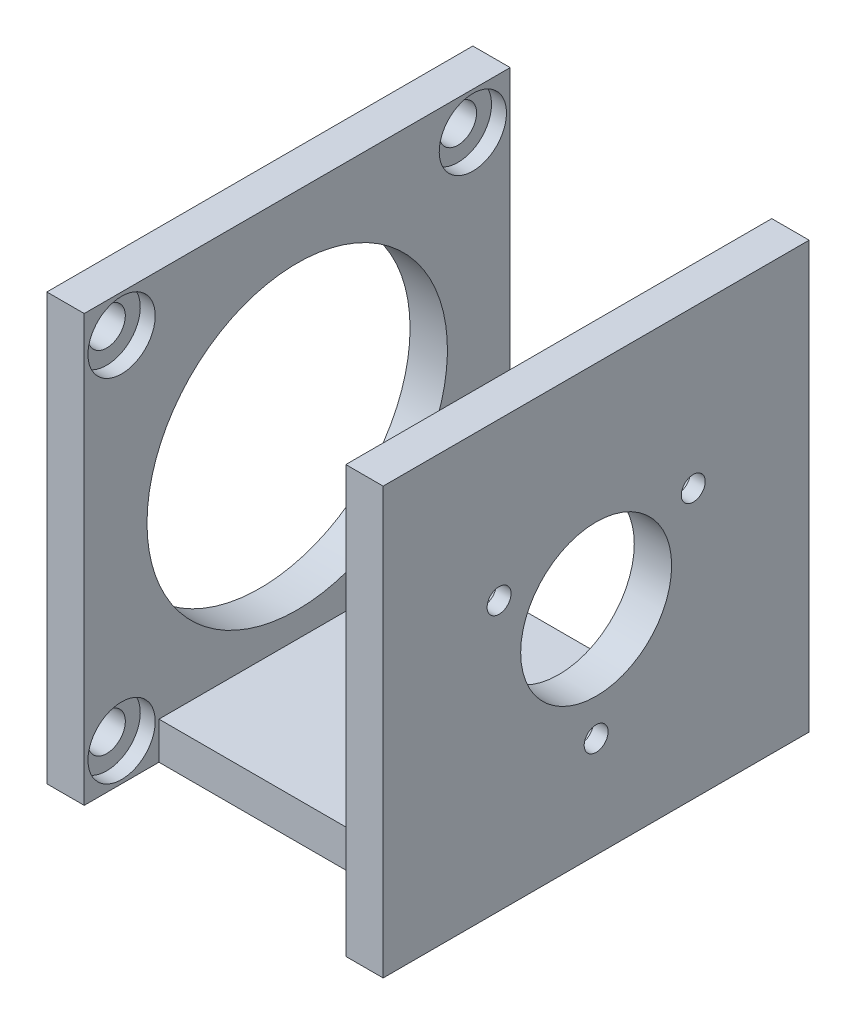
SolidWorks part; units mm, degrees
ref_plane "前视基准面" through (0, 0, 0) normal (0, 0, 1) x (1, 0, 0)
ref_plane "上视基准面" through (0, 0, 0) normal (0, 1, 0) x (1, 0, 0)
ref_plane "右视基准面" through (0, 0, 0) normal (1, 0, 0) x (0, 0, -1)
other "Configuration Table"
sketch "草图1" plane through (0, 0, 0) normal (0, 0, 1) x (1, 0, 0)
  line L0 (0, 0) -> (0, 57)
  line L1 (0, 57) -> (5, 57)
  line L2 (5, 57) -> (5, 5)
  line L3 (5, 5) -> (40, 5)
  line L4 (40, 5) -> (40, 57)
  line L5 (40, 57) -> (45, 57)
  line L6 (45, 57) -> (45, 0)
  line L7 (45, 0) -> (0, 0)
  dimension "D1" = 5
  dimension "D2" = 5
  dimension "D3" = 57
  dimension "D4" = 35
  dimension "D5" = 5
  dimension "D6" = 57
extrude "凸台-拉伸1" add sketch "草图1" along normal blind 57
sketch "草图2" plane through (0, 5, 0) normal (0, 1, 0) x (1, 0, 0)
  line L0 (40, -57) -> (40, 0) construction
  line L1 (5, -57) -> (40, -57)
  line L2 (5, -57) -> (5, -47)
  line L3 (5, -47) -> (40, -47)
  line L4 (40, -57) -> (40, -47)
  line L5 (40, -57) -> (40, 0) construction
  line L6 (5, 0) -> (40, 0)
  line L7 (5, 0) -> (5, -10)
  line L8 (5, -10) -> (40, -10)
  line L9 (40, 0) -> (40, -10)
  dimension "D1" = 10
  dimension "D2" = 10
extrude "切除-拉伸1" cut sketch "草图2" against normal through all
sketch "草图3" plane through (0, 0, 0) normal (-1, 0, 0) x (0, 0, 1)
  line L0 (57, 0) -> (0, 0) construction
  line L3 (0, 57) -> (0, 0) construction
  circle A0 centre (28.5, 28.5) radius 20.1
  point P6 (0, 28.1279)
  point P7 (0, 28.7658)
  dimension "D1" = 40.2
  dimension "D2" = 28.5
  dimension "D3" = 28.5
extrude "切除-拉伸2" cut sketch "草图3" against normal up to next
sketch "草图4" plane through (5, 0, 0) normal (1, 0, 0) x (0, 0, -1)
  line L4 (0, 0) -> (0, 57)
  line L5 (0, 57) -> (-57, 57)
  line L6 (-57, 57) -> (-57, 0)
  line L7 (-57, 0) -> (0, 0)
  line L8 (0, 0) -> (0, 57) construction
  line L9 (0, 57) -> (-57, 57) construction
  line L10 (-57, 57) -> (-57, 0) construction
  line L11 (-57, 0) -> (0, 0) construction
  circle A0 centre (-52, 52) radius 4.5
  circle A4 centre (-28.5, 28.5) radius 20.1 construction
  circle A5 centre (-28.5, 28.5) radius 20.1 construction
  circle A9 centre (-5, 52) radius 4.5
  circle A10 centre (-5, 5) radius 4.5
  circle A11 centre (-52, 5) radius 4.5
  point P18 (-28.5, 28.5)
  dimension "D2" = 9
  dimension "D5" = 4
  dimension "D3" = 5
  dimension "D4" = 5
  dimension "D1" = 0
extrude "切除-拉伸6" cut sketch "草图4" against normal blind 2
sketch "草图5" plane through (0, 0, 0) normal (1, 0, 0) x (0, 0, -1)
  line L8 (0, 0) -> (0, 57) construction
  line L9 (0, 57) -> (-57, 57) construction
  line L10 (-57, 57) -> (-57, 0) construction
  line L11 (-57, 0) -> (0, 0) construction
  circle A0 centre (-52, 52) radius 2.5
  circle A1 centre (-28.5, 28.5) radius 20.1 construction
  circle A2 centre (-28.5, 28.5) radius 20.1 construction
  circle A3 centre (-5, 52) radius 2.5
  circle A4 centre (-5, 5) radius 2.5
  circle A5 centre (-52, 5) radius 2.5
  point P18 (-28.5, 28.5)
  dimension "D2" = 5
  dimension "D3" = 5
  dimension "D4" = 5
  dimension "D1" = 4
extrude "切除-拉伸7" cut sketch "草图5" along normal up to next
sketch "草图9" plane through (45, 0, 0) normal (1, 0, 0) x (0, 0, -1)
  line L0 (-57, 0) -> (0, 0) construction
  line L1 (-57, 0) -> (-57, 57) construction
  circle A0 centre (-28.5, 28.5) radius 10.1
  dimension "D1" = 20.2
  dimension "D2" = 28.5
  dimension "D3" = 28.5
extrude "切除-拉伸8" cut sketch "草图9" against normal up to next
sketch "草图" plane through (45, 0, 0) normal (1, 0, 0) x (0, 0, -1)
  circle A1 centre (-28.5, 28.5) radius 10.1
  circle A2 centre (-28.5, 28.5) radius 10.1 construction
  circle A3 centre (-28.5, 13.5) radius 1.6
  circle A4 centre (-41.4904, 36) radius 1.6
  circle A5 centre (-15.5096, 36) radius 1.6
  point P11 (-28.5, 28.5)
  dimension "D2" = 15
  dimension "D3" = 3.2
  dimension "D1" = 0
  dimension "D4" = 3
extrude "切除-拉伸9" cut sketch "草图" against normal up to next
sketch "草图12" plane through (40, 0, 0) normal (-1, 0, 0) x (0, 0, 1)
  circle A0 centre (28.5, 13.5) radius 1.6 construction
  circle A1 centre (28.5, 13.5) radius 1.6 construction
  circle A2 centre (28.5, 13.5) radius 3.1
  circle A3 centre (28.5, 28.5) radius 10.1 construction
  circle A4 centre (28.5, 28.5) radius 10.1 construction
  circle A5 centre (15.5096, 36) radius 3.1
  circle A6 centre (41.4904, 36) radius 3.1
  point P13 (28.5, 28.5)
  dimension "D1" = 6.2
  dimension "D2" = 3
extrude "切除-拉伸10" cut sketch "草图12" against normal blind 3
